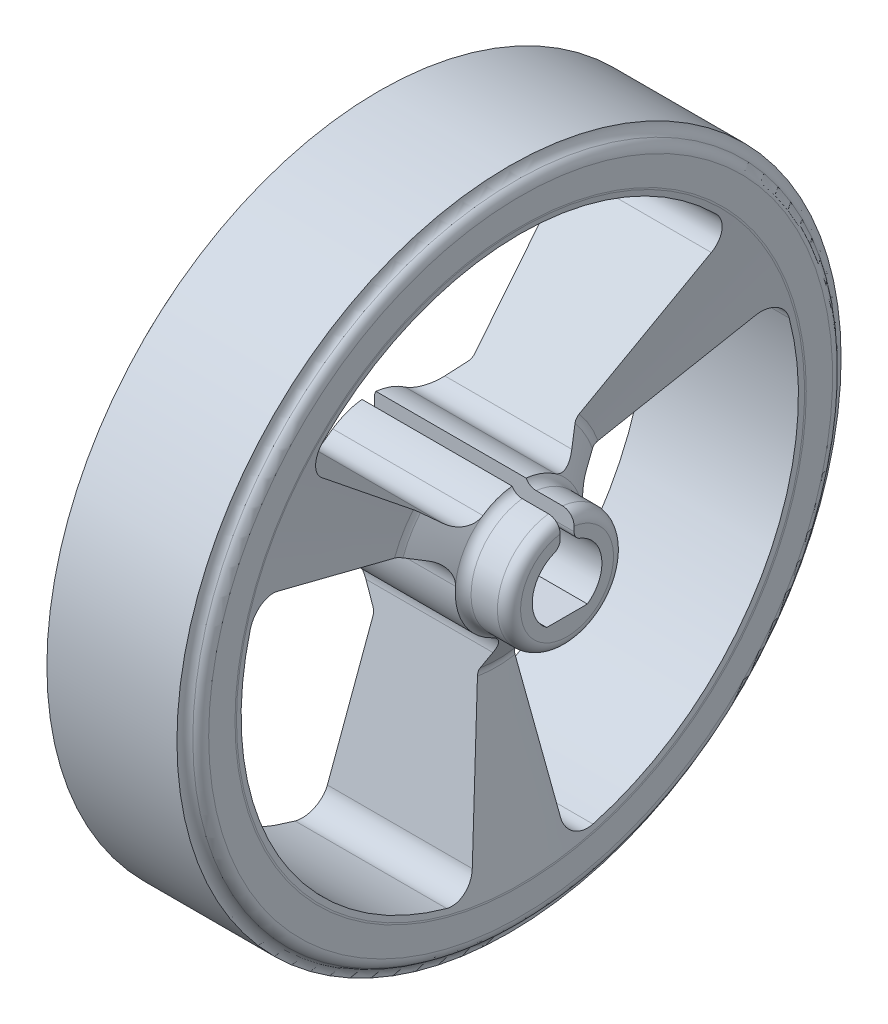
SolidWorks part; units mm, degrees
material "PBT General Purpose"
ref_plane "Front" through (0, 0, 0) normal (0, 0, 1) x (1, 0, 0)
ref_plane "Top" through (0, 0, 0) normal (0, 1, 0) x (1, 0, 0)
ref_plane "Right" through (0, 0, 0) normal (1, 0, 0) x (0, 0, -1)
sketch "Sketch1" plane through (0, 0, 0) normal (0, 1, 0) x (1, 0, 0)
  line L0 (0, 0) -> (14.3, 0) construction
  line L1 (0, 0) -> (0, 2.5)
  line L2 (0.067, 2.75) -> (0.9877, 4.3447)
  line L3 (0, 12.3) -> (0, 13.434)
  line L4 (0.5, 14.3) -> (6.1, 14.3)
  line L5 (3.3, 14.3) -> (3.3, 0) construction
  line L6 (1.05, 4.6632) -> (0.0047, 12.2316)
  line L7 (5.55, 4.6632) -> (6.5953, 12.2316)
  line L8 (6.6, 12.3) -> (6.6, 13.434)
  line L9 (6.533, 2.75) -> (5.6123, 4.3447)
  line L10 (6.966, 2.5) -> (8.1, 2.5)
  line L11 (8.6, 2) -> (8.6, 0)
  line L12 (0, 0) -> (8.6, 0)
  arc A0 (0, 2.5) -> (0.067, 2.75) centre (0.5, 2.5) cw
  arc A1 (0.9877, 4.3447) -> (1.05, 4.6632) centre (0.5547, 4.5947) ccw
  arc A2 (0.0047, 12.2316) -> (0, 12.3) centre (0.5, 12.3) cw
  arc A3 (0, 13.434) -> (0.25, 13.867) centre (0.5, 13.434) cw
  arc A4 (0.25, 13.867) -> (0.5, 14.3) centre (0, 14.3) ccw
  arc A5 (6.35, 13.867) -> (6.1, 14.3) centre (6.6, 14.3) cw
  arc A6 (6.6, 13.434) -> (6.35, 13.867) centre (6.1, 13.434) ccw
  arc A7 (6.5953, 12.2316) -> (6.6, 12.3) centre (6.1, 12.3) ccw
  arc A8 (5.6123, 4.3447) -> (5.55, 4.6632) centre (6.0453, 4.5947) cw
  arc A9 (6.533, 2.75) -> (6.966, 2.5) centre (6.966, 3) ccw
  arc A10 (8.1, 2.5) -> (8.6, 2) centre (8.1, 2) cw
  dimension "D1" = 28.6
  dimension "D2" = 0.5
  dimension "D3" = 6.6
  dimension "D4" = 5
  dimension "D5" = 4.5
  dimension "D6" = 2
  dimension "D7" = 30
  dimension "D8" = 8.6
revolve "Revolve1" add sketch "Sketch1" angle 360 about L12
sketch "Sketch2" plane through (0, 0, 0) normal (1, 0, 0) x (0, 0, -1)
  line L0 (0, 0) -> (0, 12) construction
  line L1 (8.3916, 7.0414) -> (2.7686, 2.3232)
  line L2 (0, 0) -> (10.3923, 6) construction
  line L3 (0, 0) -> (10.3923, -6) construction
  line L4 (0, 0) -> (0, -12) construction
  line L5 (0, 0) -> (-10.3923, -6) construction
  line L6 (0, 0) -> (-10.3923, 6) construction
  line L7 (-8.3916, 7.0414) -> (-2.7686, 2.3232)
  arc A0 (-2.7686, 2.3232) -> (-1.559, 2.2654) centre (-2.1259, 3.0892) ccw
  arc A1 (-8.4532, 8.5172) -> (8.4532, 8.5172) centre (0, 0) cw
  arc A2 (8.4532, 8.5172) -> (8.3916, 7.0414) centre (7.7488, 7.8074) cw
  arc A3 (-8.4532, 8.5172) -> (-8.3916, 7.0414) centre (-7.7488, 7.8074) ccw
  arc A4 (2.7686, 2.3232) -> (1.559, 2.2654) centre (2.1259, 3.0892) cw
  arc A5 (1.559, 2.2654) -> (-1.559, 2.2654) centre (0, 0) ccw
  circle A6 centre (0, 0) radius 2.75 construction
  point P19 (0, 0)
  dimension "D1" = 12
  dimension "D2" = 6
  dimension "D4" = 1
  dimension "D3" = 50
extrude "Cut-Extrude2" cut sketch "Sketch2" against normal through all and the other way through all
pattern_circular "CirPattern1" count 3 over 360 about axis through (0, 0, 0) along (1, 0, 0) of "Cut-Extrude2"
sketch "Sketch3" plane through (0, 0, 0) normal (-1, 0, 0) x (0, 0, 1)
  line L0 (0.875, -1.2183) -> (-0.875, -1.2183)
  line L1 (0.3, 1.7664) -> (0.3, 2.7336)
  line L2 (0, 0) -> (0, 2.75) construction
  line L3 (-0.3, 1.7664) -> (-0.3, 2.7336)
  arc A0 (0.875, -1.2183) -> (0.5526, 1.3945) centre (0, 0) ccw
  arc A1 (0.5526, 1.3945) -> (0.3, 1.7664) centre (0.7, 1.7664) cw
  arc A2 (1.559, 2.2654) -> (-1.559, 2.2654) centre (0, 0) ccw construction
  arc A3 (0.3, 2.7336) -> (-0.3, 2.7336) centre (0, 0) ccw
  arc A4 (-0.875, -1.2183) -> (-0.5526, 1.3945) centre (0, 0) cw
  arc A5 (-0.5526, 1.3945) -> (-0.3, 1.7664) centre (-0.7, 1.7664) ccw
  point P12 (0, -1.2183)
  dimension "D1" = 1.5
  dimension "D3" = 0.4
  dimension "D2" = 0.6
  dimension "D4" = 1.75
extrude "Cut-Extrude3" cut sketch "Sketch3" against normal through all
scale "Scale1" scale about centroid uniform scaling yes scale factor 3.6
